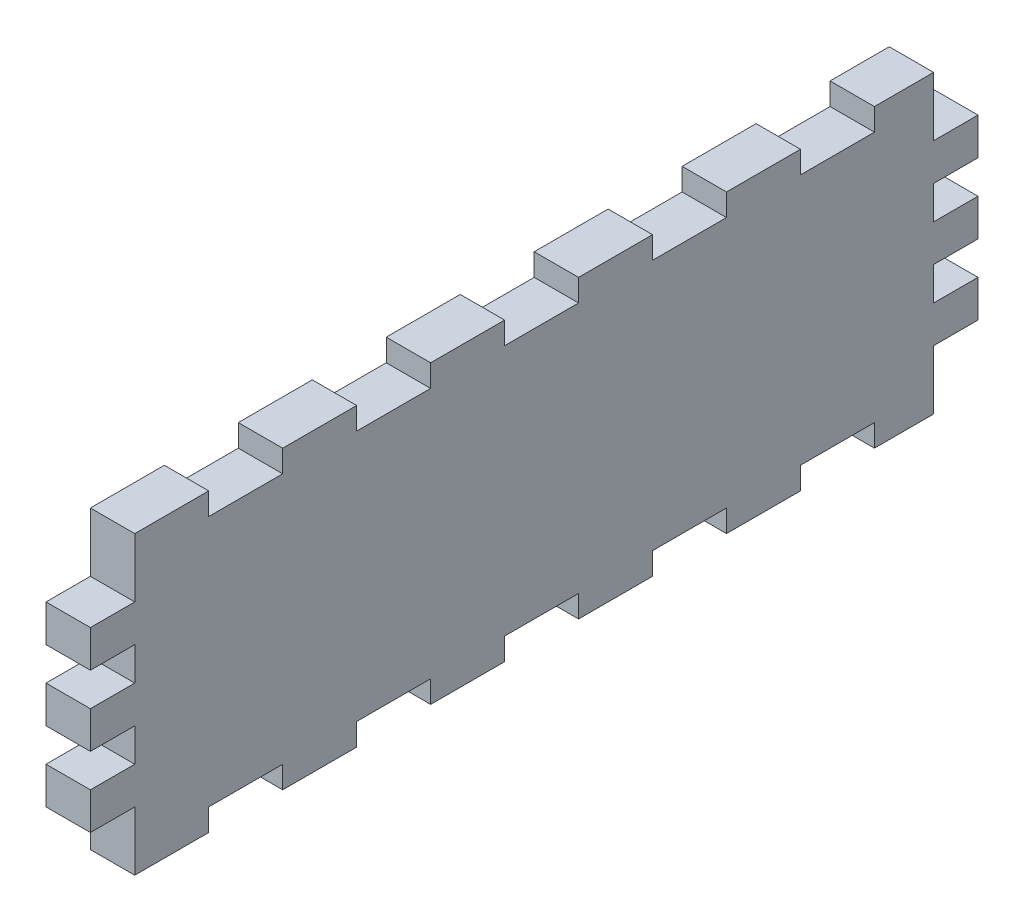
SolidWorks part; units mm, degrees
ref_plane "Спереди" through (0, 0, 0) normal (0, 0, 1) x (1, 0, 0)
ref_plane "Сверху" through (0, 0, 0) normal (0, 1, 0) x (1, 0, 0)
ref_plane "Справа" through (0, 0, 0) normal (1, 0, 0) x (0, 0, -1)
sketch "Эскиз1" plane through (0, 0, 0) normal (1, 0, 0) x (0, 0, -1)
  line L1 (0, 0) -> (108, 0)
  line L2 (0, 0) -> (0, -40)
  line L3 (0, -40) -> (108, -40)
  line L4 (108, 0) -> (108, -40)
  dimension "D1" = 40
  dimension "D2" = 108
extrude "Бобышка-Вытянуть2" add sketch "Эскиз1" along normal blind 6
sketch "Эскиз3" plane through (0, 0, 0) normal (0, 0, 1) x (1, 0, 0)
  line L0 (0, 0) -> (0, -40) construction
  line L1 (0, -8) -> (6, -8)
  line L2 (0, -8) -> (0, -13)
  line L3 (0, -13) -> (6, -13)
  line L4 (6, -8) -> (6, -13)
  line L5 (6, 0) -> (6, -40) construction
  line L6 (6, 0) -> (0, 0) construction
  line L7 (0, -17.5) -> (6, -17.5)
  line L8 (0, -17.5) -> (0, -22.5)
  line L9 (0, -22.5) -> (6, -22.5)
  line L10 (6, -17.5) -> (6, -22.5)
  line L11 (0, -27) -> (6, -27)
  line L12 (0, -27) -> (0, -32)
  line L13 (0, -32) -> (6, -32)
  line L14 (6, -27) -> (6, -32)
  line L15 (6, -40) -> (0, -40) construction
  dimension "D1" = 5
  dimension "D2" = 5
  dimension "D3" = 5
  dimension "D4" = 4.5
  dimension "D5" = 8
  dimension "D6" = 8
extrude "Бобышка-Вытянуть3" add sketch "Эскиз3" along normal blind 6
sketch "Эскиз4" plane through (0, 0, -108) normal (0, 0, -1) x (-1, 0, 0)
  line L0 (-6, -40) -> (-6, 0) construction
  line L1 (-6, -8) -> (0, -8)
  line L2 (-6, -8) -> (-6, -13)
  line L3 (-6, -13) -> (0, -13)
  line L4 (0, -8) -> (0, -13)
  line L5 (0, -40) -> (0, 0) construction
  line L6 (-6, 0) -> (0, 0) construction
  line L7 (-6, -17.5) -> (0, -17.5)
  line L8 (-6, -17.5) -> (-6, -22.5)
  line L9 (-6, -22.5) -> (0, -22.5)
  line L10 (0, -17.5) -> (0, -22.5)
  line L11 (-6, -27) -> (0, -27)
  line L12 (-6, -27) -> (-6, -32)
  line L13 (-6, -32) -> (0, -32)
  line L14 (0, -27) -> (0, -32)
  line L15 (-6, -40) -> (0, -40) construction
  dimension "D1" = 5
  dimension "D2" = 5
  dimension "D3" = 5
  dimension "D4" = 4.5
  dimension "D5" = 8
  dimension "D6" = 8
extrude "Бобышка-Вытянуть4" add sketch "Эскиз4" along normal blind 6
sketch "Эскиз5" plane through (0, -40, 0) normal (0, -1, 0) x (1, 0, 0)
  line L0 (0, 0) -> (0, -108) construction
  line L1 (0, -10) -> (6, -10)
  line L2 (0, -10) -> (0, -20)
  line L3 (0, -20) -> (6, -20)
  line L4 (6, -10) -> (6, -20)
  line L5 (6, 0) -> (6, -108) construction
  line L6 (6, 0) -> (0, 0) construction
  line L7 (0, -30) -> (0, -40)
  line L8 (0, -30) -> (6, -30)
  line L9 (6, -30) -> (6, -40)
  line L10 (0, -40) -> (6, -40)
  line L11 (0, -50) -> (0, -60)
  line L12 (0, -50) -> (6, -50)
  line L13 (6, -50) -> (6, -60)
  line L14 (0, -60) -> (6, -60)
  line L15 (0, -70) -> (0, -80)
  line L16 (0, -70) -> (6, -70)
  line L17 (6, -70) -> (6, -80)
  line L18 (0, -80) -> (6, -80)
  line L19 (0, -90) -> (0, -100)
  line L20 (0, -90) -> (6, -90)
  line L21 (6, -90) -> (6, -100)
  line L22 (0, -100) -> (6, -100)
  dimension "D1" = 10
  dimension "D2" = 10
  dimension "D3" = 5
extrude "Вырез-Вытянуть1" cut sketch "Эскиз5" against normal blind 4
sketch "Эскиз6" plane through (0, -36, 0) normal (0, -1, 0) x (1, 0, 0)
  line L1 (0, -10) -> (6, -10)
  line L2 (0, -10) -> (0, -20)
  line L3 (0, -20) -> (6, -20)
  line L4 (6, -10) -> (6, -20)
extrude "Бобышка-Вытянуть5" add sketch "Эскиз6" along normal blind 1
pattern_linear "Линейный массив1" count 5 spacing 20 along (0, 0, -1) of "Бобышка-Вытянуть5"
sketch "Эскиз8" plane through (0, 0, 0) normal (0, 1, 0) x (1, 0, 0)
  line L0 (0, 108) -> (0, 0) construction
  line L1 (0, 20) -> (6, 20)
  line L2 (0, 20) -> (0, 10)
  line L3 (0, 10) -> (6, 10)
  line L4 (6, 20) -> (6, 10)
  line L5 (6, 108) -> (6, 0) construction
  line L6 (6, 0) -> (0, 0) construction
  line L7 (0, 40) -> (0, 30)
  line L8 (0, 40) -> (6, 40)
  line L9 (6, 40) -> (6, 30)
  line L10 (0, 30) -> (6, 30)
  line L11 (0, 60) -> (0, 50)
  line L12 (0, 60) -> (6, 60)
  line L13 (6, 60) -> (6, 50)
  line L14 (0, 50) -> (6, 50)
  line L15 (0, 80) -> (0, 70)
  line L16 (0, 80) -> (6, 80)
  line L17 (6, 80) -> (6, 70)
  line L18 (0, 70) -> (6, 70)
  line L19 (0, 100) -> (0, 90)
  line L20 (0, 100) -> (6, 100)
  line L21 (6, 100) -> (6, 90)
  line L22 (0, 90) -> (6, 90)
  dimension "D1" = 10
  dimension "D2" = 10
  dimension "D3" = 5
extrude "Вырез-Вытянуть2" cut sketch "Эскиз8" against normal blind 3
